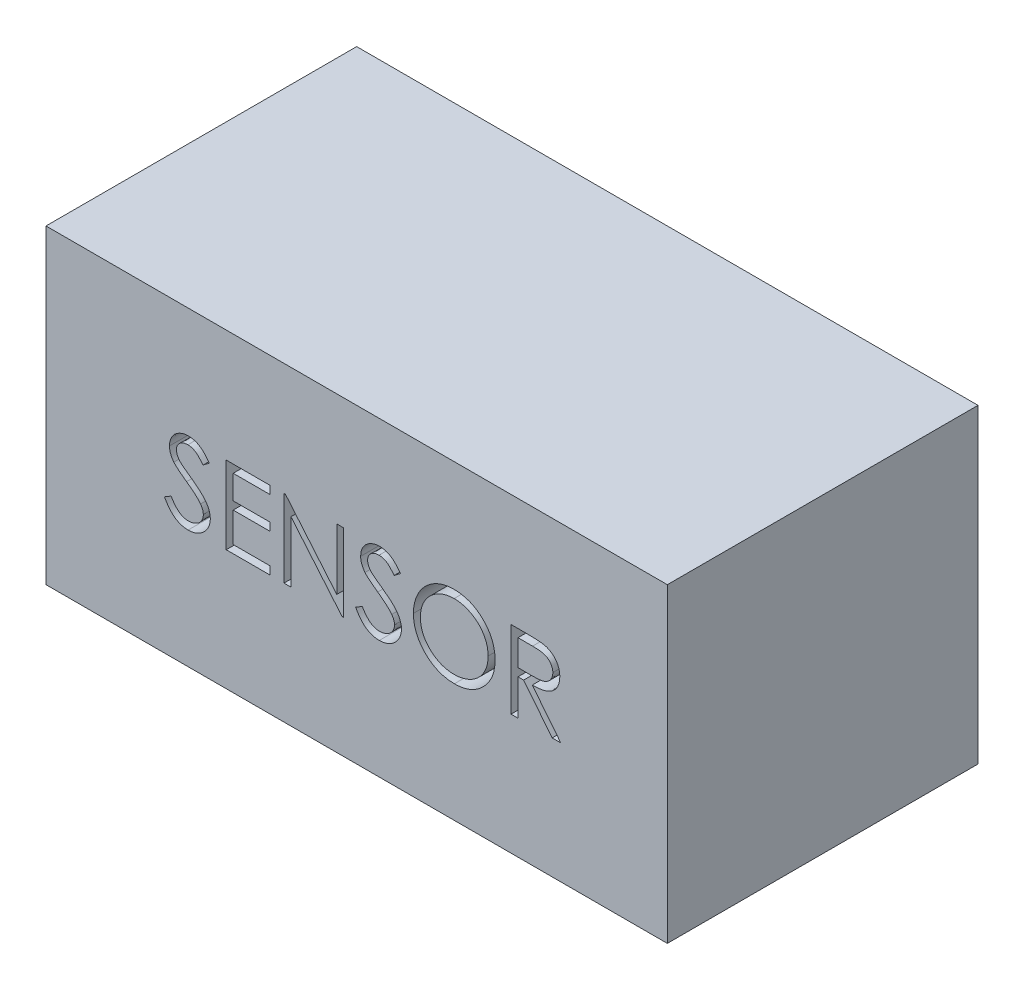
SolidWorks part; units mm, degrees
ref_plane "Front Plane" through (0, 0, 0) normal (0, 0, 1) x (1, 0, 0)
ref_plane "Top Plane" through (0, 0, 0) normal (0, 1, 0) x (1, 0, 0)
ref_plane "Right Plane" through (0, 0, 0) normal (1, 0, 0) x (0, 0, -1)
sketch "Sketch1" plane through (0, 0, 0) normal (1, 0, 0) x (0, 0, -1)
  line L1 (-42.1371, 20.5639) -> (34.0629, 20.5639)
  line L2 (-42.1371, 20.5639) -> (-42.1371, -55.6361)
  line L3 (-42.1371, -55.6361) -> (34.0629, -55.6361)
  line L4 (34.0629, 20.5639) -> (34.0629, -55.6361)
  dimension "D1" = 76.2
  dimension "D2" = 76.2
extrude "Boss-Extrude1" add sketch "Sketch1" along normal blind 152.4
sketch "Sketch2" plane through (0, 0, 42.1371) normal (0, 0, 1) x (1, 0, 0)
  text T0 "SENSOR" font "Century Gothic" height in points 72
  point P1 (22.7652, -21.1504)
  point P2 (28.5765, -26.1112)
extrude "Cut-Extrude1" cut sketch "Sketch2" against normal blind 10
